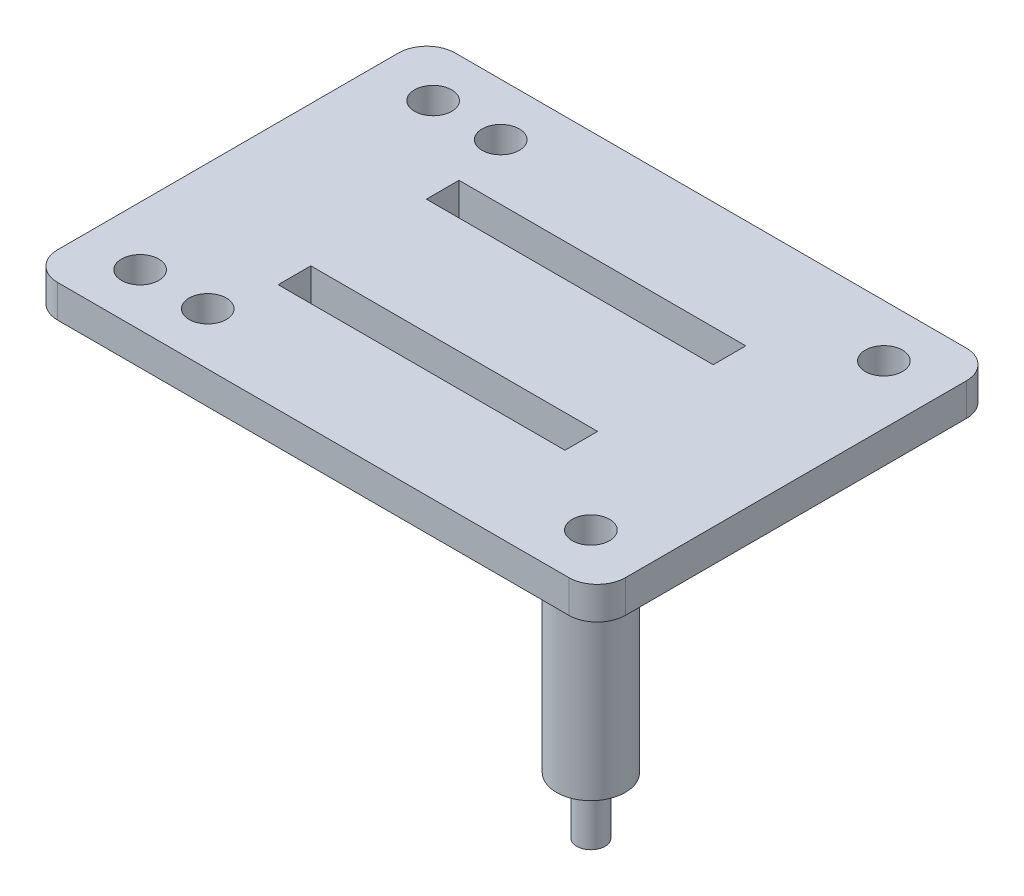
SolidWorks part; units mm, degrees
other "下垫片"
ref_plane "前视基准面" through (0, 0, 0) normal (0, 0, 1) x (1, 0, 0)
ref_plane "上视基准面" through (0, 0, 0) normal (0, 1, 0) x (1, 0, 0)
ref_plane "右视基准面" through (0, 0, 0) normal (1, 0, 0) x (0, 0, -1)
other "Configuration Table"
sketch "草图1" plane through (0, 0, 0) normal (0, 1, 0) x (1, 0, 0)
  line L0 (-89.3251, 0) -> (102.0425, 0) construction
  line L1 (0, 56.7239) -> (0, -62.578) construction
  line L2 (-20.2, -8.1375) -> (20.2, -8.1375)
  line L3 (-20.2, 12.7375) -> (20.2, 12.7375)
  line L4 (-20.2, 12.7375) -> (-20.2, 8.1375)
  line L5 (-20.2, 8.1375) -> (20.2, 8.1375)
  line L6 (20.2, 12.7375) -> (20.2, 8.1375)
  line L7 (-20.2, 12.7375) -> (20.2, 8.1375) construction
  line L8 (-20.2, 8.1375) -> (20.2, 12.7375) construction
  line L9 (20.2, -12.7375) -> (20.2, -8.1375)
  line L10 (-20.2, -12.7375) -> (20.2, -12.7375)
  line L11 (-20.2, -12.7375) -> (-20.2, -8.1375)
  circle A0 centre (-31.75, 20.6375) radius 2.625
  circle A4 centre (31.75, 20.6375) radius 2.625
  circle A5 centre (31.75, -20.6375) radius 2.625
  circle A6 centre (-31.75, -20.6375) radius 2.625
  circle A7 centre (-22.225, 20.6375) radius 2.625
  circle A8 centre (-22.225, -20.6375) radius 2.625
  point P13 (0, 10.4375)
  dimension "D5" = 5.25
  dimension "D9" = 5.25
  dimension "D7" = 10.4375
  dimension "D6" = 5.25
  dimension "D1" = 40.4
  dimension "D2" = 31.75
  dimension "D3" = 4.6
  dimension "D4" = 20.6375
  dimension "D8" = 4.6
  dimension "D10" = 40.4
  dimension "D11" = 7.9
  dimension "D12" = 31.75
  dimension "D13" = 9.525
sketch "草图3" plane through (0, 0, 0) normal (0, 1, 0) x (1, 0, 0)
  line L1 (-40, -28) -> (40, -28)
  line L2 (-40, -28) -> (-40, 28)
  line L3 (-40, 28) -> (40, 28)
  line L4 (40, -28) -> (40, 28)
  line L5 (-40, -28) -> (40, 28) construction
  line L6 (-40, 28) -> (40, -28) construction
  point P0 (0, 0)
  dimension "D1" = 56
  dimension "D2" = 80
extrude "凸台-拉伸1" add sketch "草图3" along normal blind 4.6
extrude "切除-拉伸1" cut sketch "草图1" along normal up to surface (4.6 mm away) up to face at (0, 4.6, 0)
sketch "草图5" plane through (0, 0, 0) normal (0, -1, 0) x (1, 0, 0)
  circle A0 centre (31.75, 20.6375) radius 4.85
  dimension "D1" = 9.7
extrude "凸台-拉伸2" add sketch "草图5" along normal blind 25
sketch "草图6" plane through (0, -25, 0) normal (0, -1, 0) x (1, 0, 0)
  circle A0 centre (31.75, 20.6375) radius 2
  dimension "D1" = 4
extrude "凸台-拉伸3" add sketch "草图6" along normal blind 8
sketch "草图7" plane through (0, 4.6, 0) normal (0, 1, 0) x (1, 0, 0)
  line L0 (40, -28) -> (40, 28) construction
  line L1 (31.75, 20.6375) -> (50, 20.6375)
  line L2 (31.75, 20.6375) -> (31.75, -28.0079)
  line L3 (31.75, -28.0079) -> (50, -28.0079)
  line L4 (50, 20.6375) -> (50, -28.0079)
  dimension "D1" = 10
fillet "圆角2" radius 4 4 edges at (-40, 2.3, -28) (40, 2.3, -28) (40, 2.3, 28) (-40, 2.3, 28)
